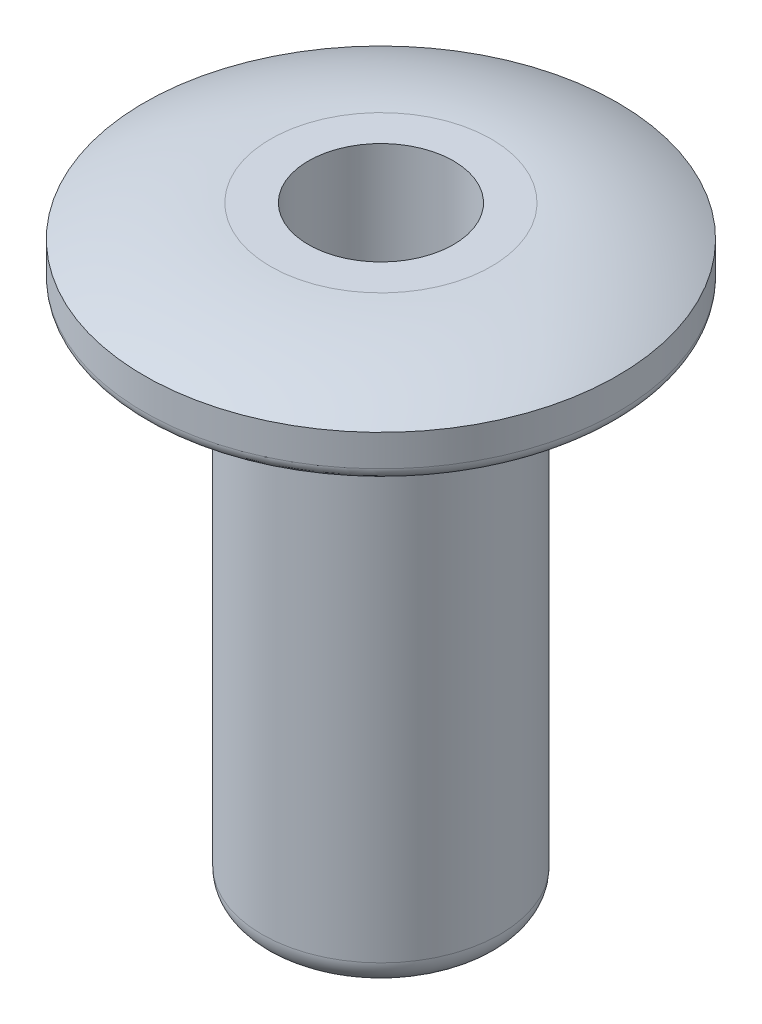
SolidWorks part; units mm, degrees
material "AISI 1010 Steel, hot rolled bar"
ref_plane "Front Plane" through (0, 0, 0) normal (0, 0, 1) x (1, 0, 0)
ref_plane "Top Plane" through (0, 0, 0) normal (0, 1, 0) x (1, 0, 0)
ref_plane "Right Plane" through (0, 0, 0) normal (1, 0, 0) x (0, 0, -1)
sketch "Sketch1" plane through (0, 0, 0) normal (0, 0, 1) x (1, 0, 0)
  line L0 (0, 0) -> (0, 26.8035) construction
  line L1 (-1.4605, 0) -> (-1.4605, 12.065)
  line L2 (-1.4605, 12.065) -> (-2.2225, 12.065)
  line L4 (-4.7625, 11.43) -> (-4.7625, 10.795)
  line L5 (-4.5085, 10.541) -> (-2.394, 10.541)
  line L6 (-2.394, 10.541) -> (-2.3939, 0)
  line L7 (-2.3939, 0) -> (-1.4605, 0)
  arc A0 (-4.7625, 10.795) -> (-4.5085, 10.541) centre (-4.5085, 10.795) ccw
  arc A1 (-2.2225, 12.065) -> (-4.7625, 11.43) centre (-2.2225, 6.6675) ccw
  dimension "D7" = 0.254
  dimension "D1" = 1.524
  dimension "D2" = 0.635
  dimension "D3" = 9.525
  dimension "D4" = 0.9335
  dimension "D5" = 2.921
  dimension "D6" = 2.54
  dimension "D8" = 12.065
revolve "Revolve1" add sketch "Sketch1" angle 360 about L0
fillet "Fillet1" radius 0.508 1 edges at (0, 0, -2.3939)
